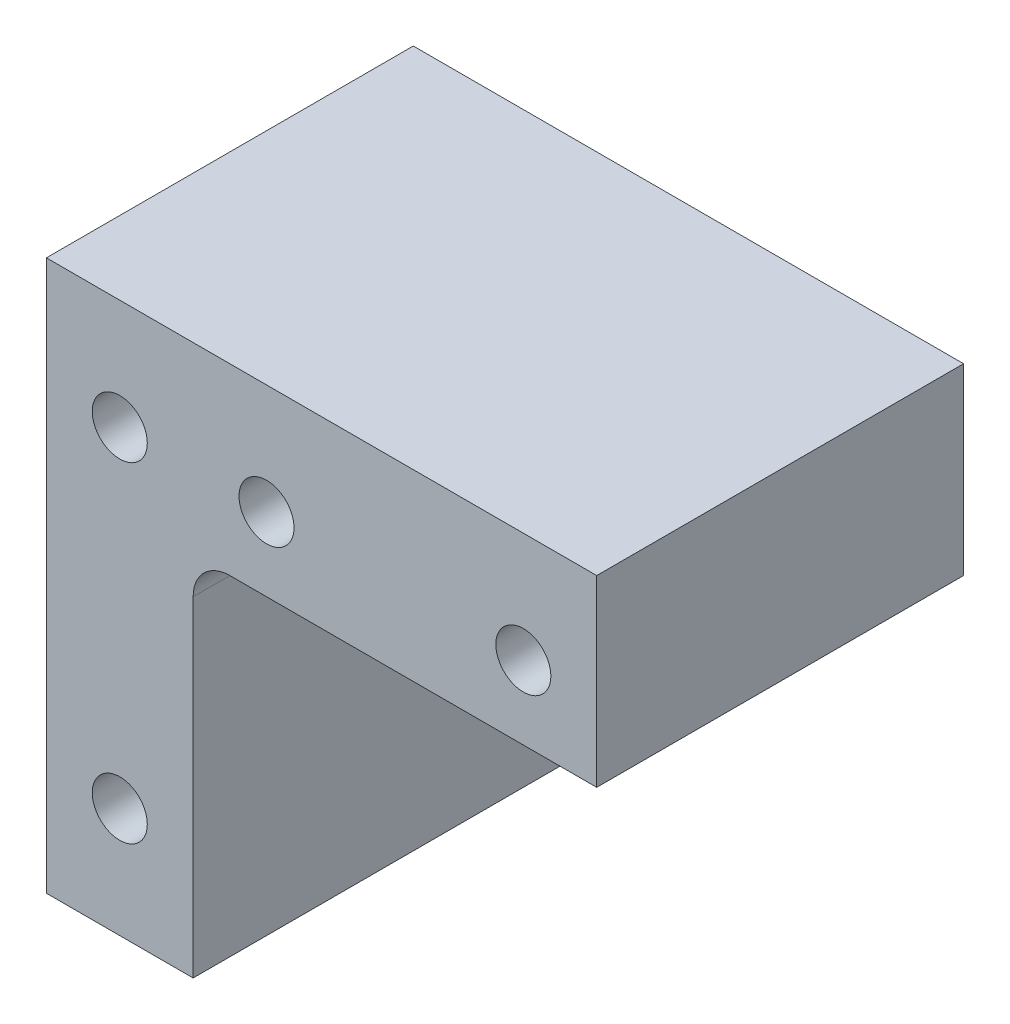
SolidWorks part; units mm, degrees
ref_plane "Front Plane" through (0, 0, 0) normal (0, 0, 1) x (1, 0, 0)
ref_plane "Top Plane" through (0, 0, 0) normal (0, 1, 0) x (1, 0, 0)
ref_plane "Right Plane" through (0, 0, 0) normal (1, 0, 0) x (0, 0, -1)
sketch "Sketch1" plane through (0, 0, 0) normal (0, 0, 1) x (1, 0, 0)
  line L0 (0, 0) -> (0, 38.1)
  line L1 (0, 38.1) -> (38.1, 38.1)
  line L2 (38.1, 38.1) -> (38.1, 25.4)
  line L3 (38.1, 25.4) -> (12.7, 25.4)
  line L4 (10.16, 22.86) -> (10.16, 0)
  line L5 (10.16, 0) -> (0, 0)
  line L6 (5.08, 0) -> (5.08, 7.62) construction
  circle A0 centre (5.08, 30.48) radius 1.905
  circle A1 centre (5.08, 7.62) radius 1.905
  circle A2 centre (15.24, 30.48) radius 1.905
  arc A3 (12.7, 25.4) -> (10.16, 22.86) centre (12.7, 22.86) ccw
  circle A4 centre (33.02, 30.48) radius 1.905
  point P16 (34.6313, 30.48)
  point P20 (10.16, 25.4)
  dimension "D1" = 3.81
  dimension "D2" = 5.08
  dimension "D8" = 2.54
  dimension "D3" = 7.62
  dimension "D4" = 7.62
  dimension "D5" = 22.86
  dimension "D6" = 12.7
  dimension "D7" = 5.08
  dimension "D9" = 38.1
  dimension "D10" = 5.08
extrude "Boss-Extrude1" add sketch "Sketch1" along normal blind 25.4
